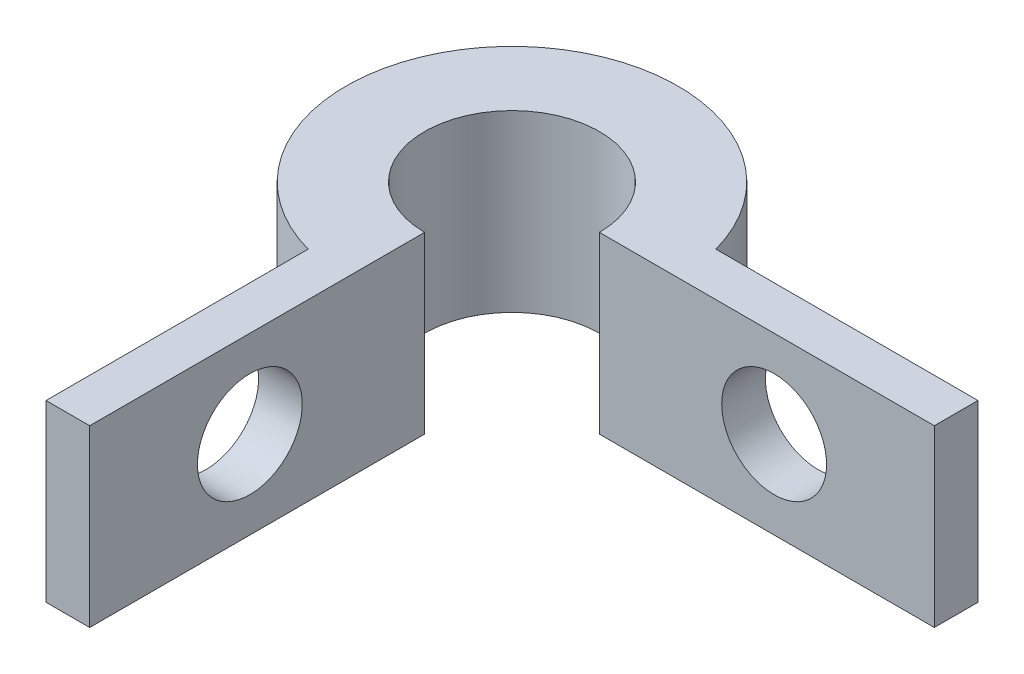
SolidWorks part; units mm, degrees
ref_plane "Front Plane" through (0, 0, 0) normal (0, 0, 1) x (1, 0, 0)
ref_plane "Top Plane" through (0, 0, 0) normal (0, 1, 0) x (1, 0, 0)
ref_plane "Right Plane" through (0, 0, 0) normal (1, 0, 0) x (0, 0, -1)
sketch "Sketch1" plane through (0, 0, 0) normal (0, 1, 0) x (1, 0, 0)
  line L0 (0, -24.1652) -> (0, -5)
  line L1 (0, -24.1652) -> (-2.5, -24.1652)
  line L2 (-2.5, -24.1652) -> (-2.5, -9.1652)
  line L3 (0, -5) -> (0, 0) construction
  line L4 (5, 0) -> (24.1652, 0)
  line L5 (24.1652, 0) -> (24.1652, 2.5)
  line L6 (24.1652, 2.5) -> (9.1652, 2.5)
  line L7 (0, 0) -> (5, 0) construction
  arc A0 (5, 0) -> (0, -5) centre (0, 0) ccw
  arc A1 (9.1652, 2.5) -> (-2.5, -9.1652) centre (0, 0) ccw
  circle A3 centre (0, 0) radius 9.5 construction
  circle A4 centre (0, 0) radius 5 construction
  point P8 (9.5, 0)
  point P17 (4.7815, 1.4619)
  dimension "D1" = 10
  dimension "D3" = 2.5
  dimension "D4" = 15
  dimension "D2" = 4.5
extrude "Boss-Extrude1" add sketch "Sketch1" along normal blind 10
sketch "Sketch2" plane through (-2.5, 0, 0) normal (-1, 0, 0) x (0, 0, 1)
  line L0 (9.1652, 5) -> (15, 5) construction
  line L1 (9.1652, 10) -> (9.1652, 0) construction
  circle A0 centre (15, 5) radius 3
  dimension "D2" = 6
  dimension "D1" = 15
extrude "Cut-Extrude1" cut sketch "Sketch2" against normal through all
pattern_circular "CirPattern1" count 2 over 90 about axis through (0, 10, 0) along (0, -1, 0) of "Cut-Extrude1"
